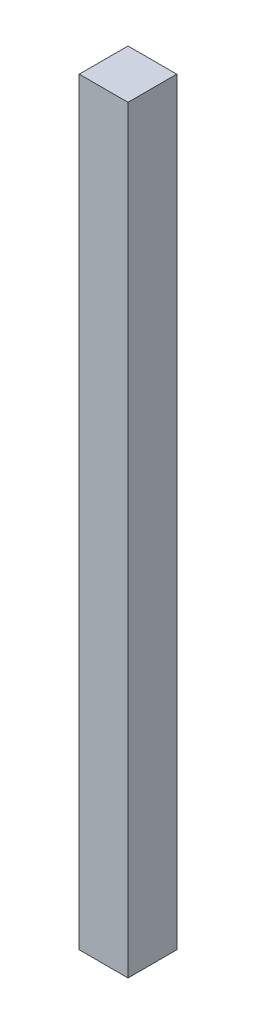
SolidWorks part; units mm, degrees
ref_plane "Front Plane" through (0, 0, 0) normal (0, 0, 1) x (1, 0, 0)
ref_plane "Top Plane" through (0, 0, 0) normal (0, 1, 0) x (1, 0, 0)
ref_plane "Right Plane" through (0, 0, 0) normal (1, 0, 0) x (0, 0, -1)
sketch "Sketch1" plane through (0, 0, 0) normal (0, 1, 0) x (1, 0, 0)
  line L1 (0, 0) -> (20, 0)
  line L2 (0, 0) -> (0, 20)
  line L3 (0, 20) -> (20, 20)
  line L4 (20, 0) -> (20, 20)
  dimension "D1" = 20
  dimension "D2" = 20
extrude "Boss-Extrude1" add sketch "Sketch1" along normal blind 311
